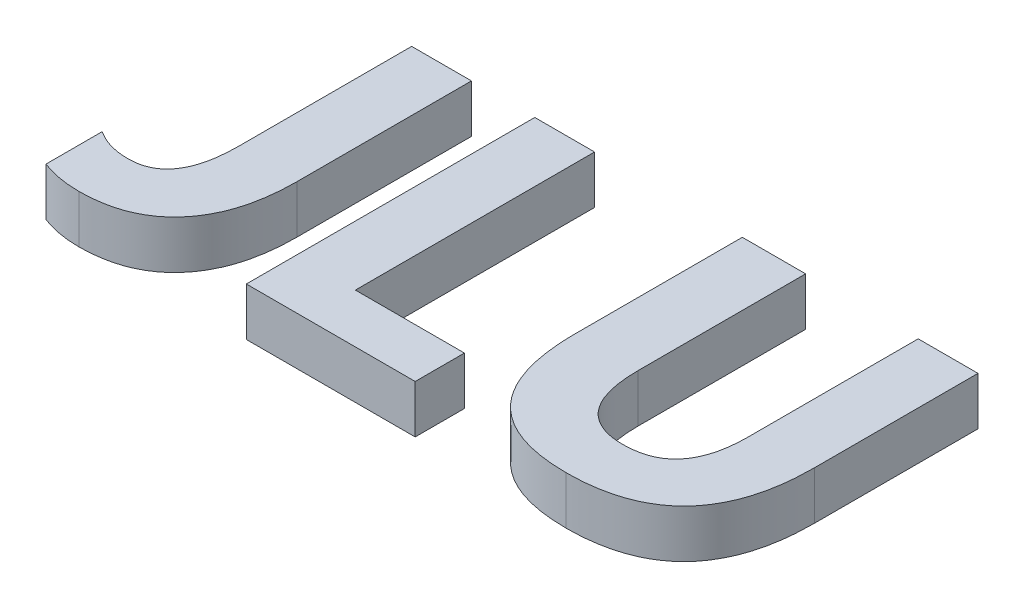
SolidWorks part; units mm, degrees
ref_plane "前视基准面" through (0, 0, 0) normal (0, 0, 1) x (1, 0, 0)
ref_plane "上视基准面" through (0, 0, 0) normal (0, 1, 0) x (1, 0, 0)
ref_plane "右视基准面" through (0, 0, 0) normal (1, 0, 0) x (0, 0, -1)
other "Configuration Table"
sketch "草图1" plane through (0, 0, 0) normal (0, 1, 0) x (1, 0, 0)
  text T0 "JLU" font "微软雅黑" height 30
extrude "凸台-拉伸1" add sketch "草图1" along normal blind 5
